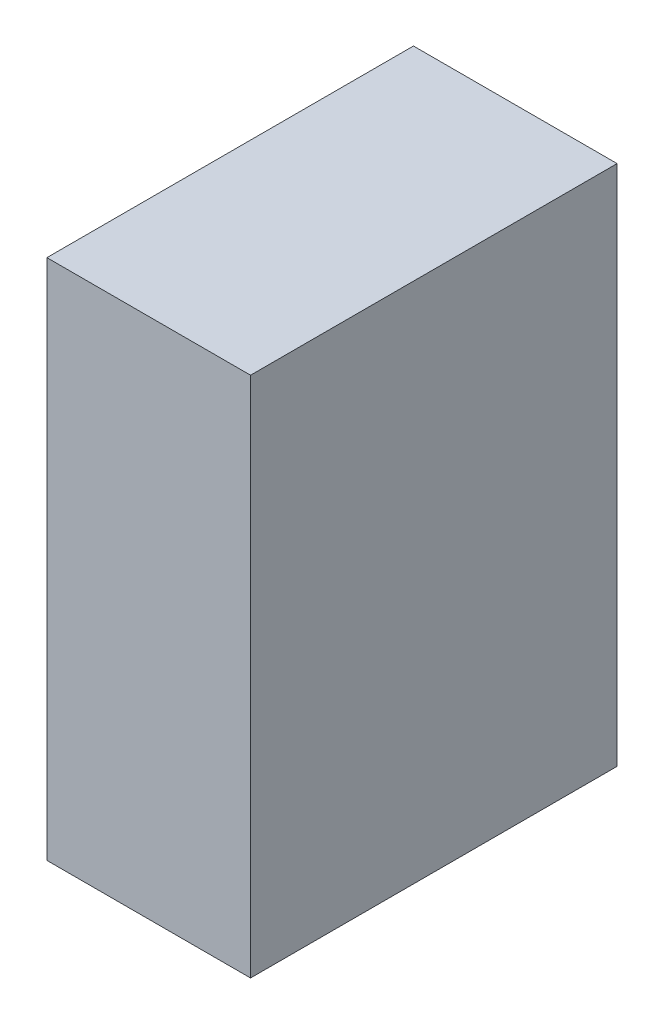
SolidWorks part; units mm, degrees
ref_plane "Спереди" through (0, 0, 0) normal (0, 0, 1) x (1, 0, 0)
ref_plane "Сверху" through (0, 0, 0) normal (0, 1, 0) x (1, 0, 0)
ref_plane "Справа" through (0, 0, 0) normal (1, 0, 0) x (0, 0, -1)
sketch "Эскиз1" plane through (0, 0, 0) normal (1, 0, 0) x (0, 0, -1)
  line L1 (-9, 12.8177) -> (9, 12.8177)
  line L2 (-9, 12.8177) -> (-9, -12.8177)
  line L3 (-9, -12.8177) -> (9, -12.8177)
  line L4 (9, 12.8177) -> (9, -12.8177)
  line L5 (-9, 12.8177) -> (9, -12.8177) construction
  line L6 (-9, -12.8177) -> (9, 12.8177) construction
  point P0 (0, 0)
extrude "Вытянуть1" add sketch "Эскиз1" against normal blind 10
